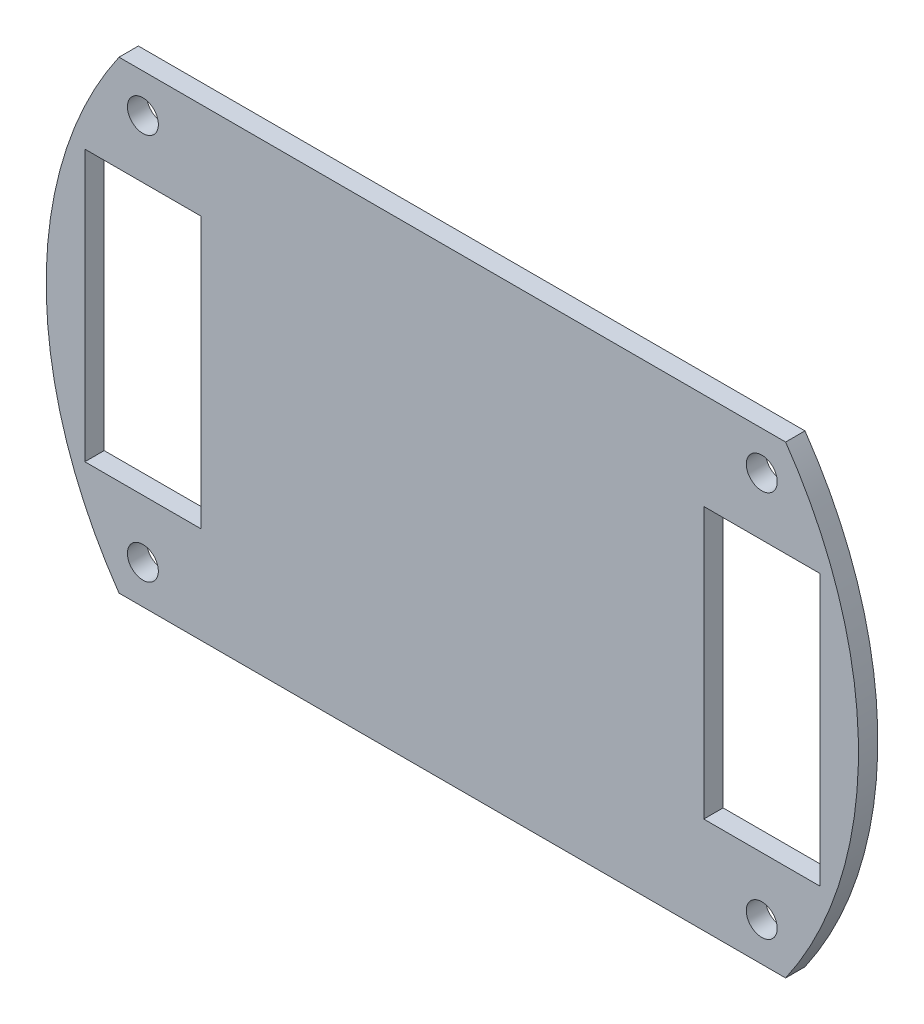
SolidWorks part; units mm, degrees
ref_plane "Plan de face" through (0, 0, 0) normal (0, 0, 1) x (1, 0, 0)
ref_plane "Plan de dessus" through (0, 0, 0) normal (0, 1, 0) x (1, 0, 0)
ref_plane "Plan de droite" through (0, 0, 0) normal (1, 0, 0) x (0, 0, -1)
sketch "Esquisse1" plane through (0, 0, 0) normal (0, 0, 1) x (1, 0, 0)
  line L0 (0, 113.8712) -> (0, -130.9268) construction
  line L1 (-95, 35) -> (-65, 35)
  line L2 (-95, 35) -> (-95, -35)
  line L3 (-95, -35) -> (-65, -35)
  line L4 (-65, 35) -> (-65, -35)
  line L5 (-95, 35) -> (-65, -35) construction
  line L6 (-95, -35) -> (-65, 35) construction
  line L7 (95, -35) -> (65, -35)
  line L8 (65, 35) -> (65, -35)
  line L9 (95, 35) -> (95, -35)
  line L10 (95, 35) -> (65, 35)
  line L11 (-121.3457, 0) -> (123.2263, 0) construction
  circle A0 centre (0, 0) radius 105
  circle A1 centre (-80, 50) radius 4
  circle A2 centre (80, 50) radius 4
  circle A3 centre (80, -50) radius 4
  circle A4 centre (-80, -50) radius 4
  point P3 (-80, 0)
  dimension "D1" = 210
  dimension "D5" = 8
  dimension "D2" = 70
  dimension "D3" = 80
  dimension "D4" = 30
  dimension "D6" = 80
  dimension "D7" = 50
extrude "Boss.-Extru.1" add sketch "Esquisse1" along normal blind 5
sketch "Esquisse2" plane through (0, 0, 5) normal (0, 0, 1) x (1, 0, 0)
  line L0 (186.3345, 0) -> (-169.5267, 0) construction
  line L1 (125, 110) -> (-125, 110)
  line L2 (125, 110) -> (125, 60)
  line L3 (125, 60) -> (-125, 60)
  line L4 (-125, 110) -> (-125, 60)
  line L5 (-125, -110) -> (-125, -60)
  line L6 (125, -60) -> (-125, -60)
  line L7 (125, -110) -> (125, -60)
  line L8 (125, -110) -> (-125, -110)
  point P4 (0, 60)
  dimension "D1" = 60
  dimension "D2" = 50
  dimension "D3" = 250
extrude "Enlèv. mat.-Extru.1" cut sketch "Esquisse2" against normal through all
